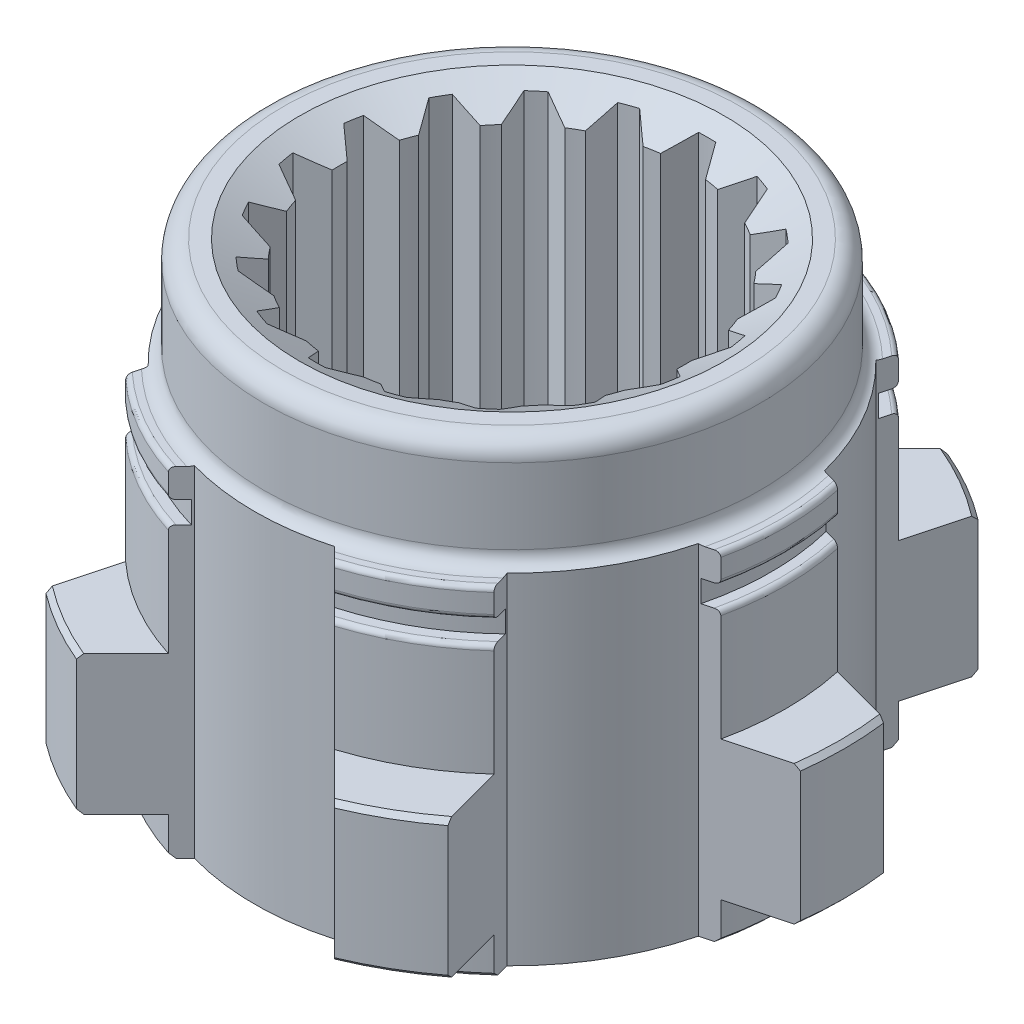
SolidWorks part; units mm, degrees
ref_plane "Plano frontal" through (0, 0, 0) normal (0, 0, 1) x (1, 0, 0)
ref_plane "Plano superior" through (0, 0, 0) normal (0, 1, 0) x (1, 0, 0)
ref_plane "Plano direito" through (0, 0, 0) normal (1, 0, 0) x (0, 0, -1)
sketch "Esboço1" plane through (0, 0, 0) normal (0, 0, 1) x (1, 0, 0)
  line L0 (0, -54.4613) -> (0, 54.4613) construction
  line L1 (18.1, 17.9937) -> (26, 17.9937)
  line L2 (26, 17.9937) -> (26, 6.5937)
  line L3 (26, 6.5937) -> (28.7, 6.5937)
  line L4 (28.7, 6.5937) -> (28.7, 3.5937)
  line L5 (28.7, 3.5937) -> (27.2, 3.5937)
  line L6 (27.2, 3.5937) -> (27.2, 1.2937)
  line L7 (27.2, 1.2937) -> (28.7, 1.2937)
  line L8 (28.7, 1.2937) -> (28.7, -10.4063)
  line L9 (28.7, -10.4063) -> (34.9, -10.4063)
  line L10 (34.9, -10.4063) -> (34.9, -25.0063)
  line L11 (34.9, -25.0063) -> (28.7, -25.0063)
  line L12 (28.7, -25.0063) -> (28.7, -29.0063)
  line L13 (28.7, -29.0063) -> (18.1, -29.0063)
  line L14 (18.1, -29.0063) -> (18.1, 17.9937)
  dimension "D1" = 18.1
  dimension "D2" = 26
  dimension "D3" = 28.7
  dimension "D4" = 28.7
  dimension "D5" = 27.2
  dimension "D6" = 34.9
  dimension "D7" = 28.7
  dimension "D8" = 4
  dimension "D9" = 14.6
  dimension "D10" = 11.7
  dimension "D11" = 2.3
  dimension "D12" = 17
  dimension "D13" = 47
revolve "Revolução1" add sketch "Esboço1" angle 360 about L0
chamfer "Chanfro2" distance 4.2 angle 30 1 edges at (0, 17.9937, -18.1)
chamfer "Chanfro3" distance 4.2 angle 30 1 edges at (0, -29.0063, -18.1)
fillet "Filete1" radius 2 1 edges at (0, 17.9937, -26)
fillet "Filete2" radius 1.5 1 edges at (0, 6.5937, -26)
fillet "Filete4" radius 0.5 3 edges at (0, 1.2937, -28.7) (0, 3.5937, -28.7) (0, 6.5937, -28.7)
chamfer "Chanfro4" distance 0.5 angle 45 3 edges at (0, -25.0063, -34.9) (0, -29.0063, -28.7) (0, -10.4063, -34.9)
sketch "Esboço2" plane through (0, -29.0063, 0) normal (0, -1, 0) x (1, 0, 0)
  line L0 (0, 0) -> (0, -27) construction
  line L1 (-7.35, -25.9803) -> (-15.8909, -34.5213)
  line L2 (7.35, -25.9803) -> (15.8909, -34.5213)
  line L3 (-26.1746, -6.6249) -> (-37.8418, -3.4987)
  line L4 (-18.8246, -19.3555) -> (-21.9508, -31.0226)
  line L5 (-18.8246, 19.3555) -> (-21.9508, 31.0226)
  line L6 (-26.1746, 6.6249) -> (-37.8418, 3.4987)
  line L7 (7.35, 25.9803) -> (15.8909, 34.5213)
  line L8 (-7.35, 25.9803) -> (-15.8909, 34.5213)
  line L9 (26.1746, 6.6249) -> (37.8418, 3.4987)
  line L10 (18.8246, 19.3555) -> (21.9508, 31.0226)
  line L11 (18.8246, -19.3555) -> (21.9508, -31.0226)
  line L12 (26.1746, -6.6249) -> (37.8418, -3.4987)
  arc A0 (-15.8909, -34.5213) -> (15.8909, -34.5213) centre (0, 23.5643) ccw
  arc A1 (-7.35, -25.9803) -> (7.35, -25.9803) centre (0, 0) ccw
  arc A2 (-37.8418, -3.4987) -> (-21.9508, -31.0226) centre (20.4073, 11.7822) ccw
  arc A3 (-26.1746, -6.6249) -> (-18.8246, -19.3555) centre (0, 0) ccw
  arc A4 (-21.9508, 31.0226) -> (-37.8418, 3.4987) centre (20.4073, -11.7822) ccw
  arc A5 (-18.8246, 19.3555) -> (-26.1746, 6.6249) centre (0, 0) ccw
  arc A6 (15.8909, 34.5213) -> (-15.8909, 34.5213) centre (0, -23.5643) ccw
  arc A7 (7.35, 25.9803) -> (-7.35, 25.9803) centre (0, 0) ccw
  arc A8 (37.8418, 3.4987) -> (21.9508, 31.0226) centre (-20.4073, -11.7822) ccw
  arc A9 (26.1746, 6.6249) -> (18.8246, 19.3555) centre (0, 0) ccw
  arc A10 (21.9508, -31.0226) -> (37.8418, -3.4987) centre (-20.4073, 11.7822) ccw
  arc A11 (18.8246, -19.3555) -> (26.1746, -6.6249) centre (0, 0) ccw
  dimension "D1" = 6
extrude "Corte-extrusão1" cut sketch "Esboço2" against normal through all
sketch "Esboço3" plane through (0, 17.9937, 0) normal (0, 1, 0) x (1, 0, 0)
  line L0 (0, 0) -> (0, 20.5) construction
  line L1 (-0.9, 20.4802) -> (-3.4138, 16.1261)
  line L2 (0.9, 20.4802) -> (3.4138, 16.1261)
  line L3 (6.1589, 19.5529) -> (2.3075, 16.3212)
  line L4 (7.8504, 18.9373) -> (8.7234, 13.986)
  line L5 (12.475, 16.2673) -> (7.7505, 14.5477)
  line L6 (13.8539, 15.1103) -> (12.9808, 10.159)
  line L7 (17.2864, 11.0195) -> (12.2587, 11.0195)
  line L8 (18.1864, 9.4607) -> (15.6726, 5.1066)
  line L9 (20.0128, 4.4427) -> (15.2883, 6.1623)
  line L10 (20.3254, 2.67) -> (16.4739, -0.5617)
  line L11 (20.3254, -2.67) -> (16.4739, 0.5617)
  line L12 (20.0128, -4.4427) -> (15.2883, -6.1623)
  line L13 (18.1864, -9.4607) -> (15.6726, -5.1066)
  line L14 (17.2864, -11.0195) -> (12.2587, -11.0195)
  line L15 (13.8539, -15.1103) -> (12.9808, -10.159)
  line L16 (12.475, -16.2673) -> (7.7505, -14.5477)
  line L17 (7.8504, -18.9373) -> (8.7234, -13.986)
  line L18 (6.1589, -19.5529) -> (2.3075, -16.3212)
  line L19 (0.9, -20.4802) -> (3.4138, -16.1261)
  line L20 (-0.9, -20.4802) -> (-3.4138, -16.1261)
  line L21 (-6.1589, -19.5529) -> (-2.3075, -16.3212)
  line L22 (-7.8504, -18.9373) -> (-8.7234, -13.986)
  line L23 (-12.475, -16.2673) -> (-7.7505, -14.5477)
  line L24 (-13.8539, -15.1103) -> (-12.9808, -10.159)
  line L25 (-17.2864, -11.0195) -> (-12.2587, -11.0195)
  line L26 (-18.1864, -9.4607) -> (-15.6726, -5.1066)
  line L27 (-20.0128, -4.4427) -> (-15.2883, -6.1623)
  line L28 (-20.3254, -2.67) -> (-16.4739, 0.5617)
  line L29 (-20.3254, 2.67) -> (-16.4739, -0.5617)
  line L30 (-20.0128, 4.4427) -> (-15.2883, 6.1623)
  line L31 (-18.1864, 9.4607) -> (-15.6726, 5.1066)
  line L32 (-17.2864, 11.0195) -> (-12.2587, 11.0195)
  line L33 (-13.8539, 15.1103) -> (-12.9808, 10.159)
  line L34 (-12.475, 16.2673) -> (-7.7505, 14.5477)
  line L35 (-7.8504, 18.9373) -> (-8.7234, 13.986)
  line L36 (-6.1589, 19.5529) -> (-2.3075, 16.3212)
  arc A0 (-3.4138, 16.1261) -> (3.4138, 16.1261) centre (0, 29.889) ccw
  arc A1 (-0.9, 20.4802) -> (0.9, 20.4802) centre (0, 0) cw
  arc A2 (2.3075, 16.3212) -> (8.7234, 13.986) centre (10.2226, 28.0865) ccw
  arc A3 (6.1589, 19.5529) -> (7.8504, 18.9373) centre (0, 0) cw
  arc A4 (7.7505, 14.5477) -> (12.9808, 10.159) centre (19.2123, 22.8963) ccw
  arc A5 (12.475, 16.2673) -> (13.8539, 15.1103) centre (0, 0) cw
  arc A6 (12.2587, 11.0195) -> (15.6726, 5.1066) centre (25.8846, 14.9445) ccw
  arc A7 (17.2864, 11.0195) -> (18.1864, 9.4607) centre (0, 0) cw
  arc A8 (15.2883, 6.1623) -> (16.4739, -0.5617) centre (29.4349, 5.1902) ccw
  arc A9 (20.0128, 4.4427) -> (20.3254, 2.67) centre (0, 0) cw
  arc A10 (16.4739, 0.5617) -> (15.2883, -6.1623) centre (29.4349, -5.1902) ccw
  arc A11 (20.3254, -2.67) -> (20.0128, -4.4427) centre (0, 0) cw
  arc A12 (15.6726, -5.1066) -> (12.2587, -11.0195) centre (25.8846, -14.9445) ccw
  arc A13 (18.1864, -9.4607) -> (17.2864, -11.0195) centre (0, 0) cw
  arc A14 (12.9808, -10.159) -> (7.7505, -14.5477) centre (19.2123, -22.8963) ccw
  arc A15 (13.8539, -15.1103) -> (12.475, -16.2673) centre (0, 0) cw
  arc A16 (8.7234, -13.986) -> (2.3075, -16.3212) centre (10.2226, -28.0865) ccw
  arc A17 (7.8504, -18.9373) -> (6.1589, -19.5529) centre (0, 0) cw
  arc A18 (3.4138, -16.1261) -> (-3.4138, -16.1261) centre (0, -29.889) ccw
  arc A19 (0.9, -20.4802) -> (-0.9, -20.4802) centre (0, 0) cw
  arc A20 (-2.3075, -16.3212) -> (-8.7234, -13.986) centre (-10.2226, -28.0865) ccw
  arc A21 (-6.1589, -19.5529) -> (-7.8504, -18.9373) centre (0, 0) cw
  arc A22 (-7.7505, -14.5477) -> (-12.9808, -10.159) centre (-19.2123, -22.8963) ccw
  arc A23 (-12.475, -16.2673) -> (-13.8539, -15.1103) centre (0, 0) cw
  arc A24 (-12.2587, -11.0195) -> (-15.6726, -5.1066) centre (-25.8846, -14.9445) ccw
  arc A25 (-17.2864, -11.0195) -> (-18.1864, -9.4607) centre (0, 0) cw
  arc A26 (-15.2883, -6.1623) -> (-16.4739, 0.5617) centre (-29.4349, -5.1902) ccw
  arc A27 (-20.0128, -4.4427) -> (-20.3254, -2.67) centre (0, 0) cw
  arc A28 (-16.4739, -0.5617) -> (-15.2883, 6.1623) centre (-29.4349, 5.1902) ccw
  arc A29 (-20.3254, 2.67) -> (-20.0128, 4.4427) centre (0, 0) cw
  arc A30 (-15.6726, 5.1066) -> (-12.2587, 11.0195) centre (-25.8846, 14.9445) ccw
  arc A31 (-18.1864, 9.4607) -> (-17.2864, 11.0195) centre (0, 0) cw
  arc A32 (-12.9808, 10.159) -> (-7.7505, 14.5477) centre (-19.2123, 22.8963) ccw
  arc A33 (-13.8539, 15.1103) -> (-12.475, 16.2673) centre (0, 0) cw
  arc A34 (-8.7234, 13.986) -> (-2.3075, 16.3212) centre (-10.2226, 28.0865) ccw
  arc A35 (-7.8504, 18.9373) -> (-6.1589, 19.5529) centre (0, 0) cw
  dimension "D1" = 18
extrude "Corte-extrusão2" cut sketch "Esboço3" against normal through all
